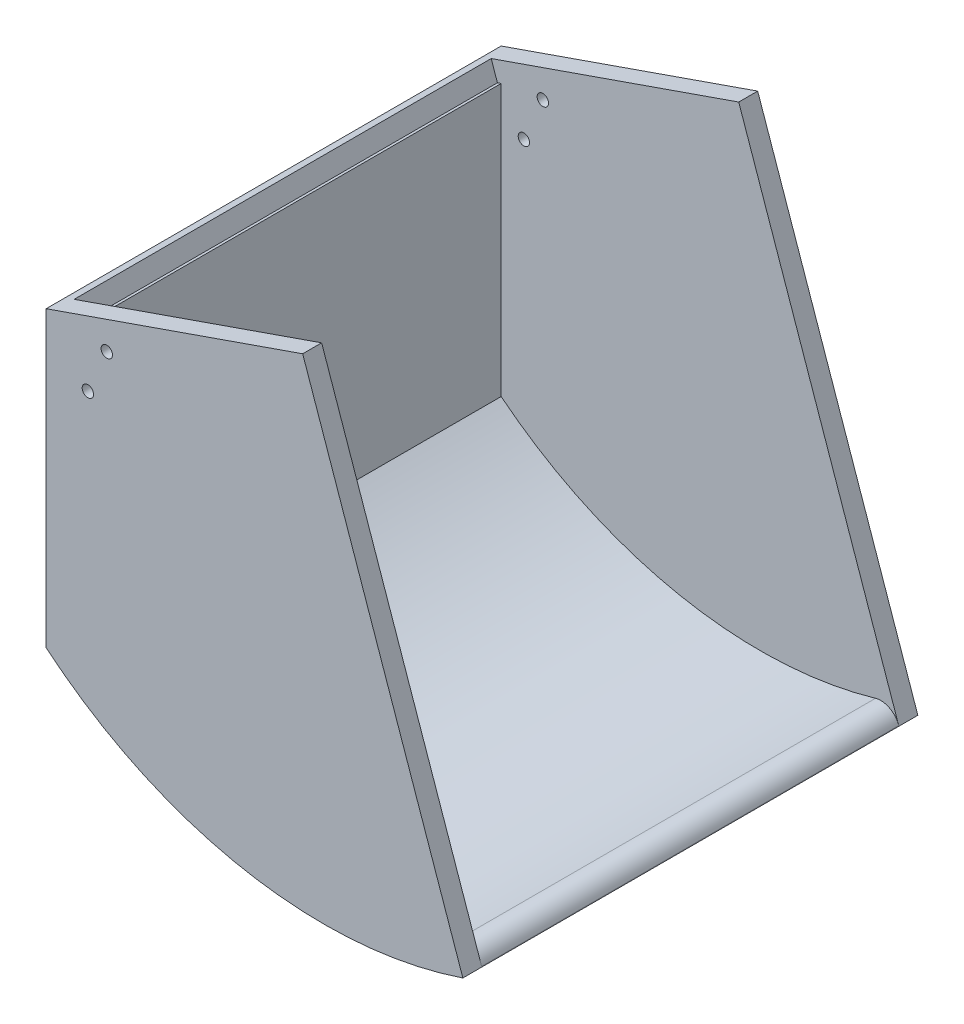
SolidWorks part; units mm, degrees
ref_plane "前视基准面" through (0, 0, 0) normal (0, 0, 1) x (1, 0, 0)
ref_plane "上视基准面" through (0, 0, 0) normal (0, 1, 0) x (1, 0, 0)
ref_plane "右视基准面" through (0, 0, 0) normal (1, 0, 0) x (0, 0, -1)
sketch "草图1" plane through (0, 0, 0) normal (0, 0, 1) x (1, 0, 0)
  line L0 (0, 0) -> (0, 71.5157)
  line L1 (0, 71.5157) -> (64.301, 93.8813)
  line L2 (64.301, 93.8813) -> (103.2604, -18.1269)
  arc A0 (0, 0) -> (103.2604, -18.1269) centre (68.2396, 85.5519) ccw
  dimension "D4" = 109.4338
  dimension "D5" = 68.2396
  dimension "D1" = 68.0797
  dimension "D2" = 70.821
  dimension "D3" = 71.5157
extrude "凸台-拉伸2" add sketch "草图1" along normal blind 110
shell "抽壳5" thickness 5
sketch "草图2" plane through (-23.833, 68.5198, 0) normal (-0.3285, 0.9445, 0) x (0.9445, 0.3285, 0)
  line L2 (91.5741, -115) -> (91.5741, 5) construction
  line L3 (91.5741, 0) -> (91.5741, -110)
  line L7 (91.5741, 0) -> (22.4564, 0)
  line L8 (22.4564, 0) -> (22.4564, -110)
  line L9 (22.4564, -110) -> (91.5741, -110)
  line L10 (91.5741, 5) -> (19.9397, 5) construction
  dimension "D1" = 69.1176
  dimension "D2" = 5
extrude "切除-拉伸2" cut sketch "草图2" against normal blind 5
sketch "草图3" plane through (0, 0, 115) normal (0, 0, 1) x (1, 0, 0)
  line L0 (-5, 75.0704) -> (-5, -2.3746) construction
  line L1 (62.6584, 98.6038) -> (-5, 75.0704) construction
  circle A0 centre (11, 73.2457) radius 1.5
  circle A1 centre (6, 61.7327) radius 1.5
  point P8 (0, 0)
  point P10 (3.7214, 61.7893)
  dimension "D1" = 3
  dimension "D2" = 3
  dimension "D3" = 16
  dimension "D4" = 6.9798
  dimension "D5" = 11
  dimension "D6" = 16.2112
extrude "切除-拉伸5" cut sketch "草图3" against normal through all both and the other way through all
fillet "圆角2" radius 5 1 edges at (103.2604, -18.1269, 55)
